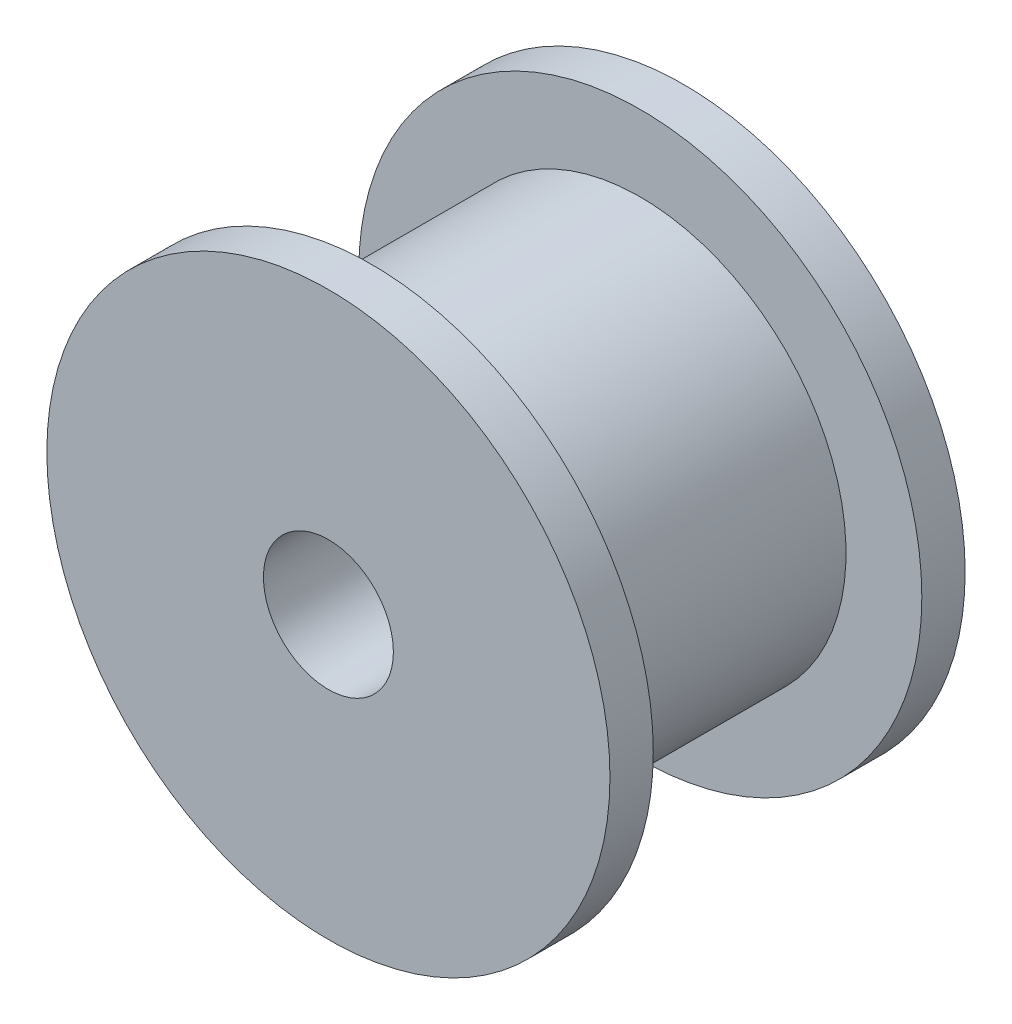
SolidWorks part; units mm, degrees
ref_plane "Plan de face" through (0, 0, 0) normal (0, 0, 1) x (1, 0, 0)
ref_plane "Plan de dessus" through (0, 0, 0) normal (0, 1, 0) x (1, 0, 0)
ref_plane "Plan de droite" through (0, 0, 0) normal (1, 0, 0) x (0, 0, -1)
sketch "Esquisse1" plane through (0, 0, 0) normal (0, 0, 1) x (1, 0, 0)
  circle A0 centre (0, 0) radius 6.5
  dimension "D1" = 13
extrude "Boss.-Extru.1" add sketch "Esquisse1" along normal blind 1
sketch "Esquisse2" plane through (0, 0, 1) normal (0, 0, 1) x (1, 0, 0)
  circle A0 centre (0, 0) radius 4.75
  dimension "D1" = 9.5
extrude "Boss.-Extru.2" add sketch "Esquisse2" along normal blind 6.2
sketch "Esquisse3" plane through (0, 0, 7.2) normal (0, 0, 1) x (1, 0, 0)
  circle A0 centre (0, 0) radius 6.5
  dimension "D1" = 13
extrude "Boss.-Extru.3" add sketch "Esquisse3" along normal blind 1
sketch "Esquisse4" plane through (0, 0, 8.2) normal (0, 0, 1) x (1, 0, 0)
  circle A0 centre (0, 0) radius 1.5
  dimension "D1" = 3
extrude "Enlèv. mat.-Extru.1" cut sketch "Esquisse4" against normal blind 10
